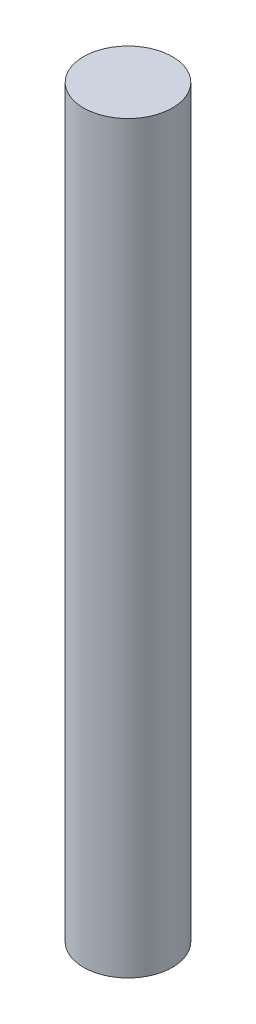
SolidWorks part; units mm, degrees
ref_plane "Front Plane" through (0, 0, 0) normal (0, 0, 1) x (1, 0, 0)
ref_plane "Top Plane" through (0, 0, 0) normal (0, 1, 0) x (1, 0, 0)
ref_plane "Right Plane" through (0, 0, 0) normal (1, 0, 0) x (0, 0, -1)
sketch "Sketch1" plane through (0, 0, 0) normal (0, 1, 0) x (1, 0, 0)
  circle A0 centre (0, 0) radius 5.08
  dimension "D1" = 10.16
extrude "Boss-Extrude1" add sketch "Sketch1" along normal blind 85.09
